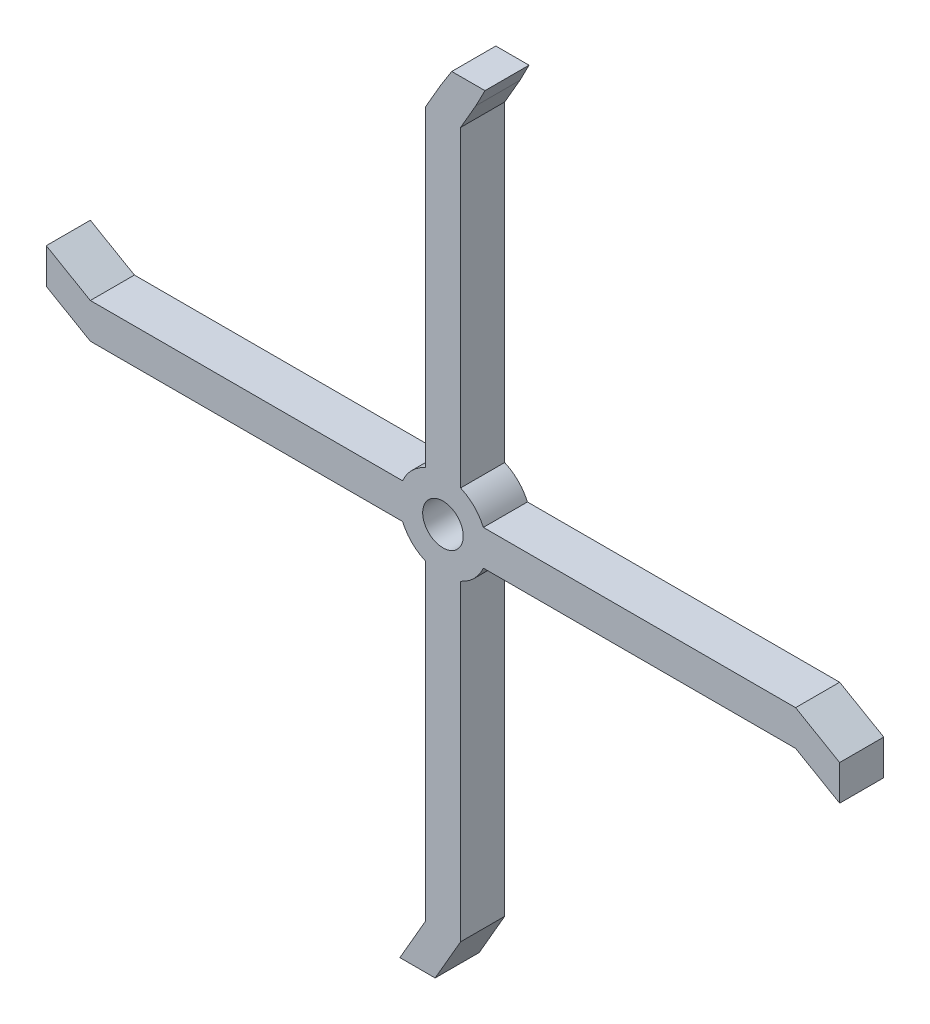
SolidWorks part; units mm, degrees
ref_plane "正面" through (0, 0, 0) normal (0, 0, 1) x (1, 0, 0)
ref_plane "平面" through (0, 0, 0) normal (0, 1, 0) x (1, 0, 0)
ref_plane "右側面" through (0, 0, 0) normal (1, 0, 0) x (0, 0, -1)
sketch "ｽｹｯﾁ1" plane through (0, 0, 0) normal (0, 0, 1) x (1, 0, 0)
  circle A0 centre (0, 0) radius 5
  circle A1 centre (0, 0) radius 2.3
extrude "ﾎﾞｽ - 押し出し1" add sketch "ｽｹｯﾁ1" along normal blind 5
sketch "ｽｹｯﾁ2" plane through (0, 0, 0) normal (0, 0, 1) x (1, 0, 0)
  line L0 (0, 0) -> (0, 40)
  line L1 (0, 0) -> (40, 0)
  line L2 (0, 0) -> (-40, 0)
  line L3 (0, 0) -> (0, -40)
  line L4 (0, 40) -> (-2, 40)
  line L5 (-2, 40) -> (-2, 4.5826)
  line L6 (-2, 4.5826) -> (2, 4.5826)
  line L7 (2, 4.5826) -> (2, 40)
  line L8 (2, 40) -> (-2, 40)
  line L9 (40, 2) -> (4.5826, 2)
  line L10 (4.5826, 2) -> (4.5826, -2)
  line L11 (4.5826, -2) -> (40, -2)
  line L12 (40, -2) -> (40, 2)
  line L13 (2, -40) -> (2, -4.5826)
  line L14 (2, -4.5826) -> (-2, -4.5826)
  line L15 (-2, -4.5826) -> (-2, -40)
  line L16 (-2, -40) -> (0, -40)
  line L17 (2, -40) -> (0, -40)
  line L18 (-40, 0) -> (-40, 2)
  line L19 (-40, 2) -> (-4.5826, 2)
  line L20 (-4.5826, 2) -> (-4.5826, -2)
  line L21 (-4.5826, -2) -> (-40, -2)
  line L22 (-40, -2) -> (-40, 2)
  line L23 (-40, 2) -> (-45, 4.8868)
  line L24 (-45, 4.8868) -> (-45, 0.8868)
  line L25 (-45, 0.8868) -> (-40, -2)
  line L26 (-2, 40) -> (-0.2717, 42.9934)
  line L27 (-0.2717, 42.9934) -> (3.7283, 42.9934)
  line L28 (3.7283, 42.9934) -> (2, 40)
  line L29 (40, 2) -> (45, -0.8868)
  line L30 (45, -0.8868) -> (45, -4.8868)
  line L31 (45, -4.8868) -> (40, -2)
  line L32 (-2, -40) -> (-4.8868, -45)
  line L33 (-4.8868, -45) -> (-0.8868, -45)
  line L34 (-0.8868, -45) -> (2, -40)
  line L35 (-0.2717, 42.9934) -> (0.9968, 45)
  line L36 (0.9968, 45) -> (4.7652, 45)
  line L37 (4.7652, 45) -> (3.7283, 42.9934)
  circle A0 centre (0, 0) radius 2
  circle A1 centre (0, 0) radius 5 construction
  dimension "D1" = 90
  dimension "D2" = 90
  dimension "D3" = 90
  dimension "D4" = 40
  dimension "D5" = 40
  dimension "D6" = 40
  dimension "D7" = 40
  dimension "D8" = 4
  dimension "D9" = 4
  dimension "D10" = 150
  dimension "D11" = 4
  dimension "D12" = 2
  dimension "D13" = 4
  dimension "D14" = 150
  dimension "D15" = 4
  dimension "D16" = 4
  dimension "D17" = 150
  dimension "D18" = 2
  dimension "D19" = 4
  dimension "D20" = 150
  dimension "D21" = 5
  dimension "D22" = 2.9934
  dimension "D23" = 5
  dimension "D24" = 5
  dimension "D25" = 5
  dimension "D26" = 40
extrude "ﾎﾞｽ - 押し出し2" add sketch "ｽｹｯﾁ2" along normal blind 5 contours L7 L8 L0 L6 | L5 L6 L0 L4 | L28 L27 L26 L4 L8 | L37 L36 L35 L27 | L20 L19 L18 L2 | L22 L21 L20 L2 | L24 L25 L22 L18 L23 | L11 L12 L1 L10 | L1 L12 L9 L10 | L31 L30 L29 L12 | L17 L13 L14 L3 | L15 L16 L3 L14 | L33 L34 L17 L16 L32
